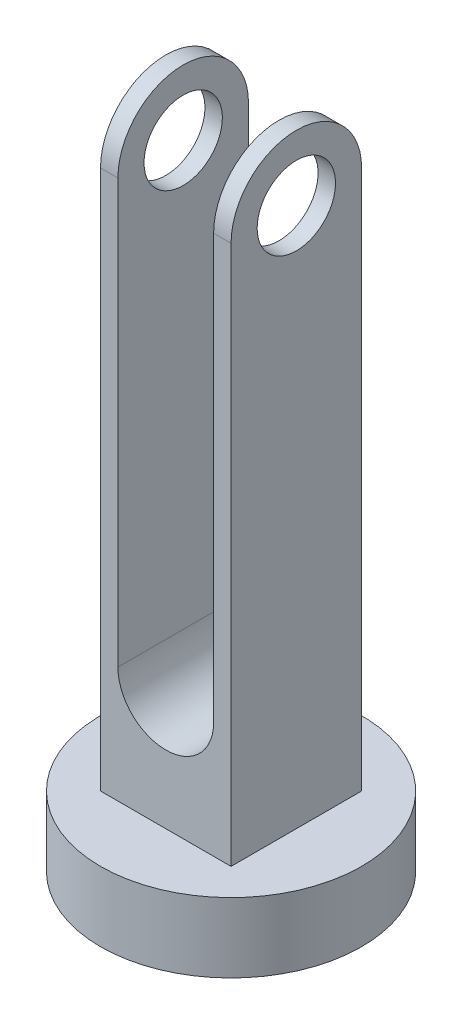
SolidWorks part; units mm, degrees
ref_plane "Front Plane" through (0, 0, 0) normal (0, 0, 1) x (1, 0, 0)
ref_plane "Top Plane" through (0, 0, 0) normal (0, 1, 0) x (1, 0, 0)
ref_plane "Right Plane" through (0, 0, 0) normal (1, 0, 0) x (0, 0, -1)
sketch "Sketch1" plane through (0, 0, 0) normal (0, 1, 0) x (1, 0, 0)
  circle A0 centre (0, 0) radius 75
  dimension "D1" = 150
extrude "Boss-Extrude1" add sketch "Sketch1" along normal blind 40
sketch "Sketch3" plane through (0, 40, 0) normal (0, 1, 0) x (1, 0, 0)
  line L1 (-37.5, -37.5) -> (37.5, -37.5)
  line L2 (-37.5, -37.5) -> (-37.5, 37.5)
  line L3 (-37.5, 37.5) -> (37.5, 37.5)
  line L4 (37.5, -37.5) -> (37.5, 37.5)
  line L5 (-37.5, -37.5) -> (37.5, 37.5) construction
  line L6 (-37.5, 37.5) -> (37.5, -37.5) construction
  point P0 (0, 0)
  dimension "D1" = 75
  dimension "D2" = 75
extrude "Boss-Extrude2" add sketch "Sketch3" along normal blind 347.5
sketch "Sketch4" plane through (-37.5, 0, 0) normal (-1, 0, 0) x (0, 0, 1)
  line L0 (-37.5, 40) -> (37.5, 40) construction
  circle A0 centre (0, 350) radius 22.5
  dimension "D2" = 45
  dimension "D1" = 310
sketch "Sketch5" plane through (-37.5, 0, 0) normal (-1, 0, 0) x (0, 0, 1)
  line L1 (-37.5, 350) -> (-37.5, 387.5)
  line L2 (-37.5, 387.5) -> (0, 387.5)
  line L3 (0, 387.5) -> (37.5, 387.5)
  line L4 (37.5, 387.5) -> (37.5, 350)
  arc A0 (37.5, 350) -> (-37.5, 350) centre (0, 350) ccw
  line M3 (37.5, 40) -> (37.5, 387.5)
  line M4 (37.5, 387.5) -> (-37.5, 387.5)
  line M5 (-37.5, 387.5) -> (-37.5, 40)
extrude "Cut-Extrude1" cut sketch "Sketch5" against normal blind 80 contours A0 M3 M4 | A0 M4 M5
extrude "Cut-Extrude2" cut sketch "Sketch4" against normal blind 80 contours A0
sketch "Sketch6" plane through (0, 0, 37.5) normal (0, 0, 1) x (1, 0, 0)
  line L0 (-37.5, 350) -> (-37.5, 40) construction
  line L5 (27.5, 401.5776) -> (-27.5, 401.5776)
  line L6 (27.5, 401.5776) -> (27.5, 106.6612)
  line L8 (-27.5, 401.5776) -> (-27.5, 106.6612)
  line L9 (37.5, 350) -> (37.5, 40) construction
  arc A0 (-27.5, 106.6612) -> (27.5, 106.6612) centre (0, 106.6612) ccw
  point P0 (0, 209.8207)
  dimension "D1" = 10
  dimension "D2" = 294.9164
  dimension "D3" = 10
extrude "Cut-Extrude3" cut sketch "Sketch6" against normal blind 80
